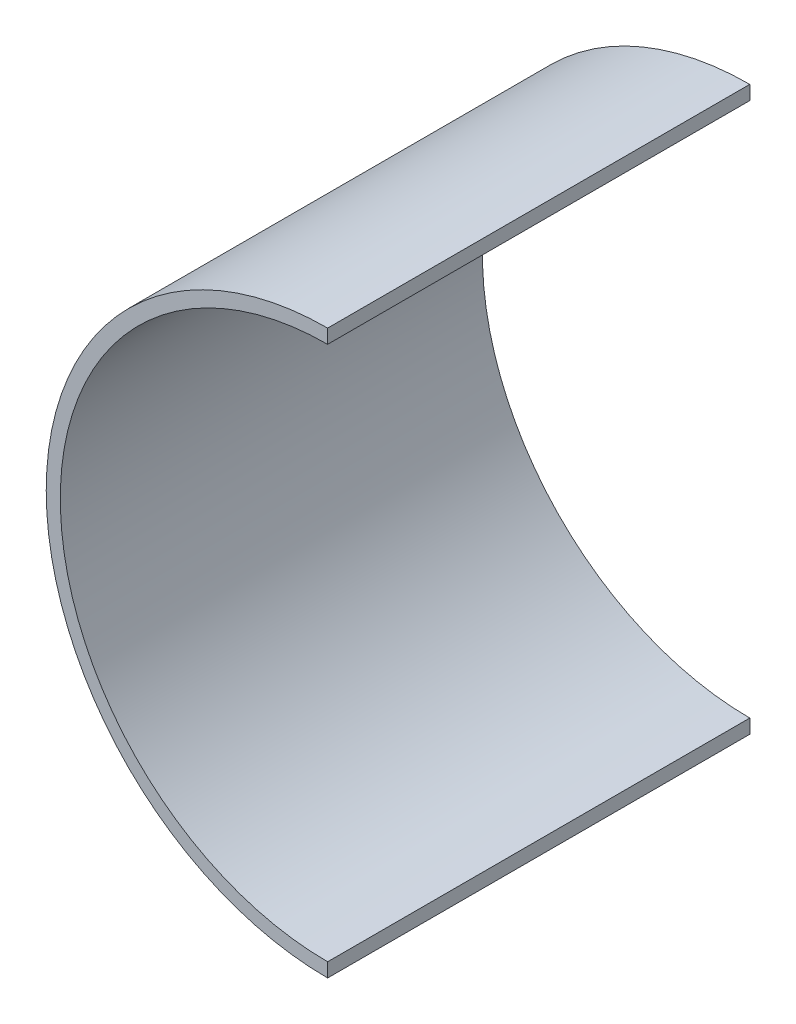
SolidWorks part; units mm, degrees
ref_plane "Спереди" through (0, 0, 0) normal (0, 0, 1) x (1, 0, 0)
ref_plane "Сверху" through (0, 0, 0) normal (0, 1, 0) x (1, 0, 0)
ref_plane "Справа" through (0, 0, 0) normal (1, 0, 0) x (0, 0, -1)
other "Configuration Table"
sketch "Эскиз1" plane through (0, 0, 0) normal (0, 0, 1) x (1, 0, 0)
  line L0 (0, 40) -> (0, -40)
  circle A0 centre (0, 0) radius 40
  circle A1 centre (0, 0) radius 38
  dimension "D1" = 80
  dimension "D2" = 2
extrude "Бобышка-Вытянуть1" add sketch "Эскиз1" along normal blind 20 contours A1 L0 A0
sketch "Эскиз2" plane through (0, 0, 20) normal (0, 0, 1) x (1, 0, 0)
  line L0 (0, -38) -> (0, -40)
  line L1 (0, -38) -> (0, -40)
  line L2 (0, 40) -> (0, 38)
  line L3 (0, 40) -> (0, 38)
  arc A0 (0, 40) -> (0, -40) centre (0, 0) ccw
  arc A1 (0, 40) -> (0, -40) centre (0, 0) ccw
  arc A2 (0, 38) -> (0, -38) centre (0, 0) ccw
  arc A3 (0, 38) -> (0, -38) centre (0, 0) ccw
extrude "Бобышка-Вытянуть2" add sketch "Эскиз2" along normal blind 40
